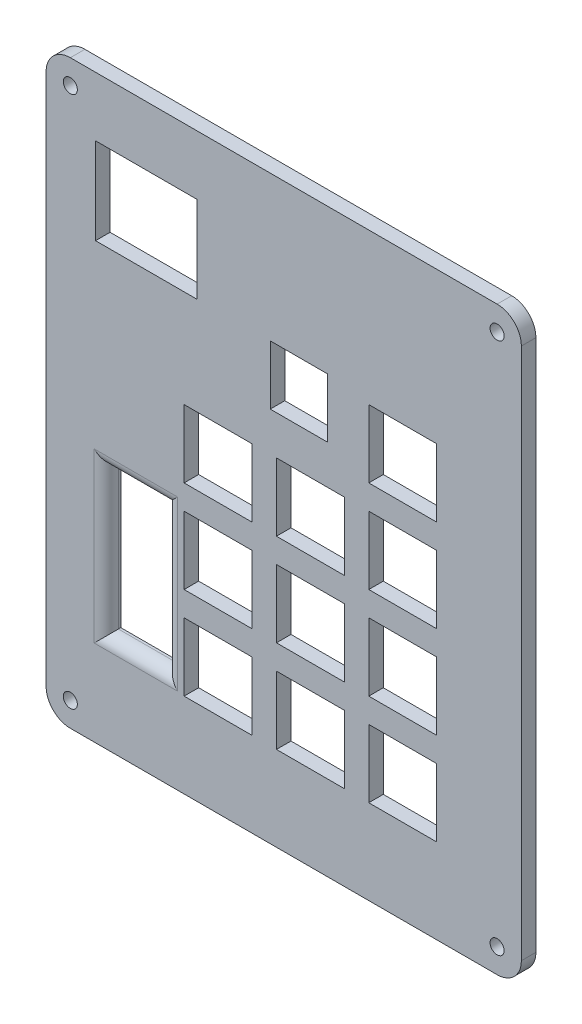
SolidWorks part; units mm, degrees
ref_plane "Front Plane" through (0, 0, 0) normal (1, 0, 0) x (0, 1, 0)
ref_plane "Top Plane" through (0, 0, 0) normal (0, 0, 1) x (0, 1, 0)
ref_plane "Right Plane" through (0, 0, 0) normal (0, 1, 0) x (-1, 0, 0)
sketch "Sketch5" plane through (0, 0, 0) normal (0, 0, 1) x (0, 1, 0)
  line L0 (0.0951, 57.4075) -> (76.2953, 57.4075) construction
  line L1 (76.2953, 57.4075) -> (76.2953, 0.2577) construction
  line L2 (76.2953, 0.2577) -> (0.0951, 0.2577) construction
  line L3 (0.0951, 0.2577) -> (0.0951, 57.4075) construction
  line L4 (2.6197, 16.7832) -> (16.6192, 16.7832) construction
  line L5 (16.6192, 16.7832) -> (16.6192, 2.7836) construction
  line L6 (16.6192, 2.7836) -> (2.6197, 2.7836) construction
  line L7 (2.6197, 2.7836) -> (2.6197, 16.7832) construction
  line L8 (21.6697, 16.7832) -> (35.6692, 16.7832) construction
  line L9 (35.6692, 16.7832) -> (35.6692, 2.7836) construction
  line L10 (35.6692, 2.7836) -> (21.6697, 2.7836) construction
  line L11 (21.6697, 2.7836) -> (21.6697, 16.7832) construction
  line L12 (40.7197, 16.7832) -> (54.7193, 16.7832) construction
  line L13 (54.7193, 16.7832) -> (54.7193, 2.7836) construction
  line L14 (54.7193, 2.7836) -> (40.7197, 2.7836) construction
  line L15 (40.7197, 2.7836) -> (40.7197, 16.7832) construction
  line L16 (59.7697, 16.7832) -> (73.7693, 16.7832) construction
  line L17 (73.7693, 16.7832) -> (73.7693, 2.7836) construction
  line L18 (73.7693, 2.7836) -> (59.7697, 2.7836) construction
  line L19 (59.7697, 2.7836) -> (59.7697, 16.7832) construction
  line L20 (2.6197, 35.8332) -> (16.6192, 35.8332) construction
  line L21 (16.6192, 35.8332) -> (16.6192, 21.8336) construction
  line L22 (16.6192, 21.8336) -> (2.6197, 21.8336) construction
  line L23 (2.6197, 21.8336) -> (2.6197, 35.8332) construction
  line L24 (21.6697, 35.8332) -> (35.6692, 35.8332) construction
  line L25 (35.6692, 35.8332) -> (35.6692, 21.8336) construction
  line L26 (35.6692, 21.8336) -> (21.6697, 21.8336) construction
  line L27 (21.6697, 21.8336) -> (21.6697, 35.8332) construction
  line L28 (40.7197, 35.8332) -> (54.7193, 35.8332) construction
  line L29 (54.7193, 35.8332) -> (54.7193, 21.8336) construction
  line L30 (54.7193, 21.8336) -> (40.7197, 21.8336) construction
  line L31 (40.7197, 21.8336) -> (40.7197, 35.8332) construction
  line L32 (2.6197, 54.8834) -> (16.6192, 54.8834) construction
  line L33 (16.6192, 54.8834) -> (16.6192, 40.8838) construction
  line L34 (16.6192, 40.8838) -> (2.6197, 40.8838) construction
  line L35 (2.6197, 40.8838) -> (2.6197, 54.8834) construction
  line L36 (21.6697, 54.8834) -> (35.6692, 54.8834) construction
  line L37 (35.6692, 54.8834) -> (35.6692, 40.8838) construction
  line L38 (35.6692, 40.8838) -> (21.6697, 40.8838) construction
  line L39 (21.6697, 40.8838) -> (21.6697, 54.8834) construction
  line L40 (40.7197, 54.8834) -> (54.7193, 54.8834) construction
  line L41 (54.7193, 54.8834) -> (54.7193, 40.8838) construction
  line L42 (54.7193, 40.8838) -> (40.7197, 40.8838) construction
  line L43 (40.7197, 40.8838) -> (40.7197, 54.8834) construction
  line L44 (28.6695, 35.8332) -> (28.6695, 21.8336) construction
  line L45 (35.6692, 28.8334) -> (21.6697, 28.8334) construction
  dimension "D1" = 13.9995
  dimension "D2" = 5.0505
  dimension "D3" = 5.0505
  dimension "D4" = 5.0505
  dimension "D5" = 5.0507
  dimension "D6" = 5.0504
  dimension "D7" = 21.576
  dimension "D8" = 5.0505
  dimension "D9" = 5.0504
  dimension "D10" = 2.526
  dimension "D11" = 2.5259
  dimension "D12" = 2.5241
  dimension "D13" = 2.5246
sketch "Sketch6" plane through (0, 0, 0) normal (0, 0, 1) x (0, 1, 0)
  line L0 (19.1445, 19.3084) -> (19.1445, 0.2584) construction
  line L5 (0.0945, 19.3084) -> (19.1445, 19.3084) construction
  line L6 (0.0945, 19.3084) -> (0.0945, 0.2584) construction
  line L7 (0.0945, 0.2584) -> (19.1445, 0.2584) construction
  line L8 (19.1445, 19.3084) -> (19.1445, 0.2584) construction
  line L9 (19.1445, 19.3084) -> (38.1945, 19.3084) construction
  line L10 (38.1945, 19.3084) -> (38.1945, 0.2584) construction
  line L11 (19.1445, 0.2584) -> (38.1945, 0.2584) construction
  line L12 (38.1945, 19.3084) -> (38.1945, 0.2584) construction
  line L13 (38.1945, 19.3084) -> (57.2445, 19.3084) construction
  line L14 (57.2445, 19.3084) -> (57.2445, 0.2584) construction
  line L15 (38.1945, 0.2584) -> (57.2445, 0.2584) construction
  line L16 (19.1445, 38.3584) -> (19.1445, 19.3084) construction
  line L17 (19.1445, 38.3584) -> (38.1945, 38.3584) construction
  line L18 (38.1945, 38.3584) -> (38.1945, 19.3084) construction
  line L19 (19.1445, 19.3084) -> (38.1945, 19.3084) construction
  line L20 (38.1945, 38.3584) -> (38.1945, 19.3084) construction
  line L21 (38.1945, 38.3584) -> (57.2445, 38.3584) construction
  line L22 (57.2445, 38.3584) -> (57.2445, 19.3084) construction
  line L23 (38.1945, 19.3084) -> (57.2445, 19.3084) construction
  line L24 (19.1445, 57.4084) -> (19.1445, 38.3584) construction
  line L25 (19.1445, 57.4084) -> (38.1945, 57.4084) construction
  line L26 (38.1945, 57.4084) -> (38.1945, 38.3584) construction
  line L27 (19.1445, 38.3584) -> (38.1945, 38.3584) construction
  line L28 (38.1945, 57.4084) -> (38.1945, 38.3584) construction
  line L29 (38.1945, 57.4084) -> (57.2445, 57.4084) construction
  line L30 (57.2445, 57.4084) -> (57.2445, 38.3584) construction
  line L31 (38.1945, 38.3584) -> (57.2445, 38.3584) construction
  line L32 (0.0945, 38.3584) -> (0.0945, 19.3084) construction
  line L33 (0.0945, 38.3584) -> (19.1445, 38.3584) construction
  line L34 (19.1445, 38.3584) -> (19.1445, 19.3084) construction
  line L35 (0.0945, 19.3084) -> (19.1445, 19.3084) construction
  line L36 (0.0945, 57.4084) -> (0.0945, 38.3584) construction
  line L37 (0.0945, 57.4084) -> (19.1445, 57.4084) construction
  line L38 (19.1445, 57.4084) -> (19.1445, 38.3584) construction
  line L39 (0.0945, 38.3584) -> (19.1445, 38.3584) construction
  line L40 (19.1445, 38.3584) -> (38.1945, 19.3084) construction
  line L41 (57.2445, 19.3084) -> (76.2945, 19.3084) construction
  line L42 (57.2445, 19.3084) -> (57.2445, 0.2584) construction
  line L43 (57.2445, 0.2584) -> (76.2945, 0.2584) construction
  line L44 (76.2945, 19.3084) -> (76.2945, 0.2584) construction
  line L45 (38.1945, 38.3584) -> (19.1445, 19.3084) construction
  line L47 (28.6695, 35.8332) -> (28.6695, 21.8336) construction
  line L48 (35.6692, 21.8336) -> (21.6697, 21.8336) construction
  line L49 (-4.6655, 73.1584) -> (94.7645, 73.1584) construction
  line L50 (-4.6655, 73.1584) -> (-4.6655, -4.5016) construction
  line L51 (-4.6655, -4.5016) -> (94.7645, -4.5016) construction
  line L52 (94.7645, 73.1584) -> (94.7645, -4.5016) construction
  line L53 (62.7945, 37.1084) -> (74.9945, 37.1084)
  line L54 (62.7945, 37.1084) -> (62.7945, 25.3084)
  line L55 (62.7945, 25.3084) -> (74.9945, 25.3084)
  line L56 (74.9945, 37.1084) -> (74.9945, 25.3084)
  line L57 (21.6697, 21.8336) -> (21.6697, 35.8332) construction
  line L58 (21.6697, 35.8332) -> (35.6692, 35.8332) construction
  line L59 (35.6692, 35.8332) -> (35.6692, 21.8336) construction
  line L60 (54.7193, 35.8332) -> (54.7193, 21.8336) construction
  line L61 (40.7197, 35.8332) -> (54.7193, 35.8332) construction
  line L62 (40.7197, 21.8336) -> (40.7197, 35.8332) construction
  line L63 (54.7193, 21.8336) -> (40.7197, 21.8336) construction
  line L64 (59.7697, 16.7832) -> (73.7693, 16.7832) construction
  line L65 (73.7693, 16.7832) -> (73.7693, 2.7836) construction
  line L66 (73.7693, 2.7836) -> (59.7697, 2.7836) construction
  line L67 (59.7697, 2.7836) -> (59.7697, 16.7832) construction
  line L68 (54.7193, 16.7832) -> (54.7193, 2.7836) construction
  line L69 (54.7193, 2.7836) -> (40.7197, 2.7836) construction
  line L70 (40.7197, 2.7836) -> (40.7197, 16.7832) construction
  line L71 (40.7197, 16.7832) -> (54.7193, 16.7832) construction
  line L72 (21.6697, 2.7836) -> (21.6697, 16.7832) construction
  line L73 (21.6697, 16.7832) -> (35.6692, 16.7832) construction
  line L74 (35.6692, 16.7832) -> (35.6692, 2.7836) construction
  line L75 (35.6692, 2.7836) -> (21.6697, 2.7836) construction
  line L76 (2.6197, 2.7836) -> (2.6197, 16.7832) construction
  line L77 (16.6192, 2.7836) -> (2.6197, 2.7836) construction
  line L78 (16.6192, 16.7832) -> (16.6192, 2.7836) construction
  line L79 (2.6197, 16.7832) -> (16.6192, 16.7832) construction
  line L80 (2.6197, 21.8336) -> (2.6197, 35.8332) construction
  line L81 (2.6197, 35.8332) -> (16.6192, 35.8332) construction
  line L82 (16.6192, 35.8332) -> (16.6192, 21.8336) construction
  line L83 (16.6192, 21.8336) -> (2.6197, 21.8336) construction
  line L84 (2.6197, 54.8834) -> (16.6192, 54.8834) construction
  line L85 (2.6197, 40.8838) -> (2.6197, 54.8834) construction
  line L86 (16.6192, 40.8838) -> (2.6197, 40.8838) construction
  line L87 (16.6192, 54.8834) -> (16.6192, 40.8838) construction
  line L88 (21.6697, 54.8834) -> (35.6692, 54.8834) construction
  line L89 (21.6697, 40.8838) -> (21.6697, 54.8834) construction
  line L90 (35.6692, 40.8838) -> (21.6697, 40.8838) construction
  line L91 (35.6692, 54.8834) -> (35.6692, 40.8838) construction
  line L92 (40.7197, 40.8838) -> (40.7197, 54.8834) construction
  line L93 (54.7193, 40.8838) -> (40.7197, 40.8838) construction
  line L94 (54.7193, 54.8834) -> (54.7193, 40.8838) construction
  line L95 (40.7197, 54.8834) -> (54.7193, 54.8834) construction
  line L96 (35.6692, 21.8336) -> (21.6697, 21.8336)
  line L97 (21.6697, 21.8336) -> (21.6697, 35.8332)
  line L98 (21.6697, 35.8332) -> (35.6692, 35.8332)
  line L99 (35.6692, 35.8332) -> (35.6692, 21.8336)
  line L100 (54.7193, 35.8332) -> (54.7193, 21.8336)
  line L101 (40.7197, 35.8332) -> (54.7193, 35.8332)
  line L102 (40.7197, 21.8336) -> (40.7197, 35.8332)
  line L103 (54.7193, 21.8336) -> (40.7197, 21.8336)
  line L104 (59.7697, 16.7832) -> (73.7693, 16.7832)
  line L105 (73.7693, 16.7832) -> (73.7693, 2.7836)
  line L106 (73.7693, 2.7836) -> (59.7697, 2.7836)
  line L107 (59.7697, 2.7836) -> (59.7697, 16.7832)
  line L108 (54.7193, 16.7832) -> (54.7193, 2.7836)
  line L109 (54.7193, 2.7836) -> (40.7197, 2.7836)
  line L110 (40.7197, 2.7836) -> (40.7197, 16.7832)
  line L111 (40.7197, 16.7832) -> (54.7193, 16.7832)
  line L112 (21.6697, 2.7836) -> (21.6697, 16.7832)
  line L113 (21.6697, 16.7832) -> (35.6692, 16.7832)
  line L114 (35.6692, 16.7832) -> (35.6692, 2.7836)
  line L115 (35.6692, 2.7836) -> (21.6697, 2.7836)
  line L116 (2.6197, 2.7836) -> (2.6197, 16.7832)
  line L117 (16.6192, 2.7836) -> (2.6197, 2.7836)
  line L118 (16.6192, 16.7832) -> (16.6192, 2.7836)
  line L119 (2.6197, 16.7832) -> (16.6192, 16.7832)
  line L120 (2.6197, 21.8336) -> (2.6197, 35.8332)
  line L121 (2.6197, 35.8332) -> (16.6192, 35.8332)
  line L122 (16.6192, 35.8332) -> (16.6192, 21.8336)
  line L123 (16.6192, 21.8336) -> (2.6197, 21.8336)
  line L124 (2.6197, 54.8834) -> (16.6192, 54.8834)
  line L125 (2.6197, 40.8838) -> (2.6197, 54.8834)
  line L126 (16.6192, 40.8838) -> (2.6197, 40.8838)
  line L127 (16.6192, 54.8834) -> (16.6192, 40.8838)
  line L128 (21.6697, 54.8834) -> (35.6692, 54.8834)
  line L129 (21.6697, 40.8838) -> (21.6697, 54.8834)
  line L130 (35.6692, 40.8838) -> (21.6697, 40.8838)
  line L131 (35.6692, 54.8834) -> (35.6692, 40.8838)
  line L132 (40.7197, 40.8838) -> (40.7197, 54.8834)
  line L133 (54.7193, 40.8838) -> (40.7197, 40.8838)
  line L134 (54.7193, 54.8834) -> (54.7193, 40.8838)
  line L135 (40.7197, 54.8834) -> (54.7193, 54.8834)
  line L136 (104.9645, 83.3584) -> (104.9645, -14.7016)
  line L137 (5.3296, 70.9434) -> (35.0296, 70.9434)
  line L138 (5.3296, 70.9434) -> (5.3296, 58.7434)
  line L139 (5.3296, 58.7434) -> (35.0297, 58.7434)
  line L140 (35.0296, 70.9434) -> (35.0297, 58.7434)
  line L141 (74.8645, 73.1584) -> (92.7145, 73.1584)
  line L142 (74.8645, 73.1584) -> (74.8645, 52.2384)
  line L143 (74.8645, 52.2384) -> (92.7145, 52.2384)
  line L144 (92.7145, 73.1584) -> (92.7145, 52.2384)
  line L145 (-14.8655, -14.7016) -> (104.9645, -14.7016)
  line L146 (-14.8655, 83.3584) -> (-14.8655, -14.7016)
  line L147 (-14.8655, 83.3584) -> (104.9645, 83.3584)
  circle A0 centre (-9.8655, 78.3584) radius 1.45
  circle A1 centre (-9.8655, -9.7016) radius 1.45
  circle A2 centre (99.9645, -9.7016) radius 1.45
  circle A3 centre (99.9645, 78.3584) radius 1.45
  point P4 (28.6695, 28.8334)
  point P41 (28.6695, 28.8334)
  dimension "D24" = 2.9
  dimension "D25" = 5
  dimension "D1" = 19.05
  dimension "D4" = 19.05
  dimension "D5" = 99.43
  dimension "D6" = 77.66
  dimension "D7" = 4.76
  dimension "D8" = 4.76
  dimension "D9" = 6
  dimension "D10" = 5.55
  dimension "D11" = 12.2
  dimension "D12" = 11.8
  dimension "D13" = 12.2
  dimension "D14" = 29.7
  dimension "D15" = 1.335
  dimension "D16" = 2.71
  dimension "D17" = 17.85
  dimension "D18" = 20.92
  dimension "D19" = 2.05
  dimension "D21" = 5
  dimension "D22" = 5
  dimension "D23" = 5
  dimension "D20" = 10.2
  dimension "D2" = 3
  dimension "D3" = 3
extrude "Boss-Extrude1" add sketch "Sketch6" along normal blind 3
fillet "Fillet1" radius 5 4 edges at (-83.3584, 104.9645, 1.5) (14.7016, 104.9645, 1.5) (14.7016, -14.8655, 1.5) (-83.3584, -14.8655, 1.5)
fillet "Fillet2" radius 2.5 4 edges at (-64.8434, 35.0296, 3) (-58.7434, 20.1796, 3) (-64.8434, 5.3296, 3) (-70.9434, 20.1796, 3)
